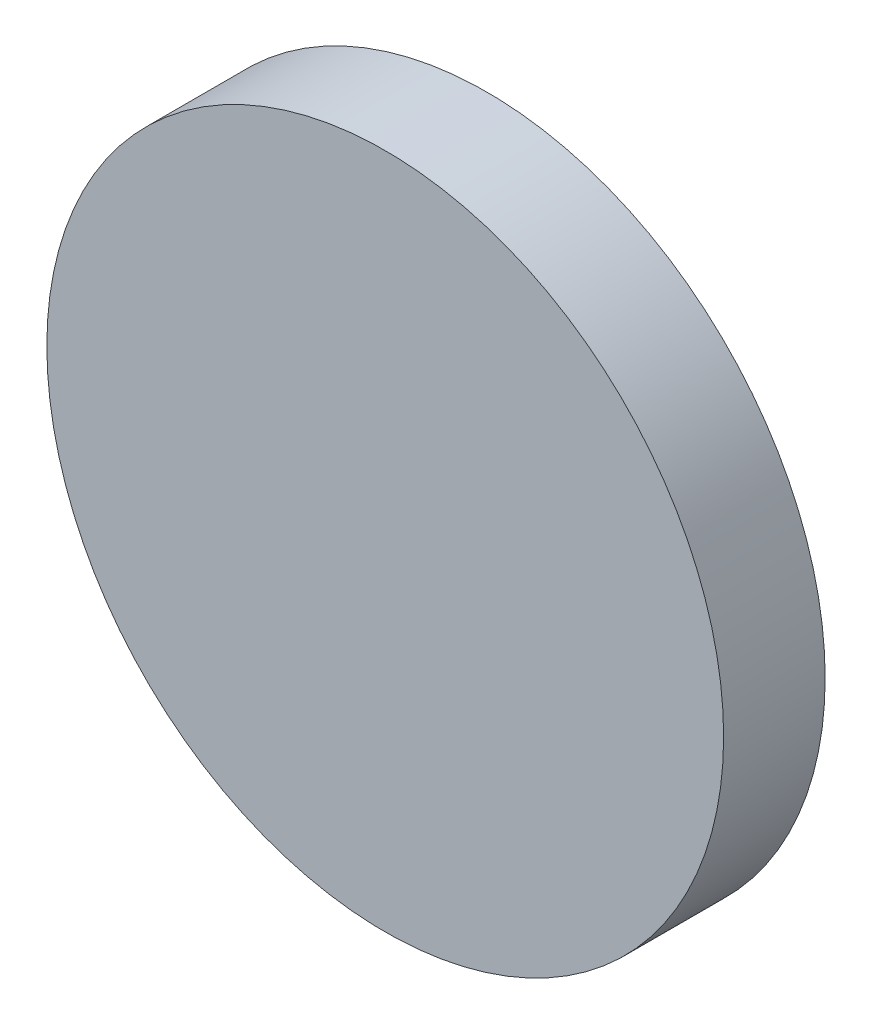
SolidWorks part; units mm, degrees
material "AISI 1015 Acier étiré à froid (SS)"
ref_plane "Plan de face" through (0, 0, 0) normal (0, 0, 1) x (1, 0, 0)
ref_plane "Plan de dessus" through (0, 0, 0) normal (0, 1, 0) x (1, 0, 0)
ref_plane "Plan de droite" through (0, 0, 0) normal (1, 0, 0) x (0, 0, -1)
sketch "Esquisse1" plane through (0, 0, 0) normal (0, 0, 1) x (1, 0, 0)
  circle A0 centre (0, 0) radius 2
  dimension "D1" = 4
extrude "Boss.-Extru.1" add sketch "Esquisse1" along normal blind 0.6
